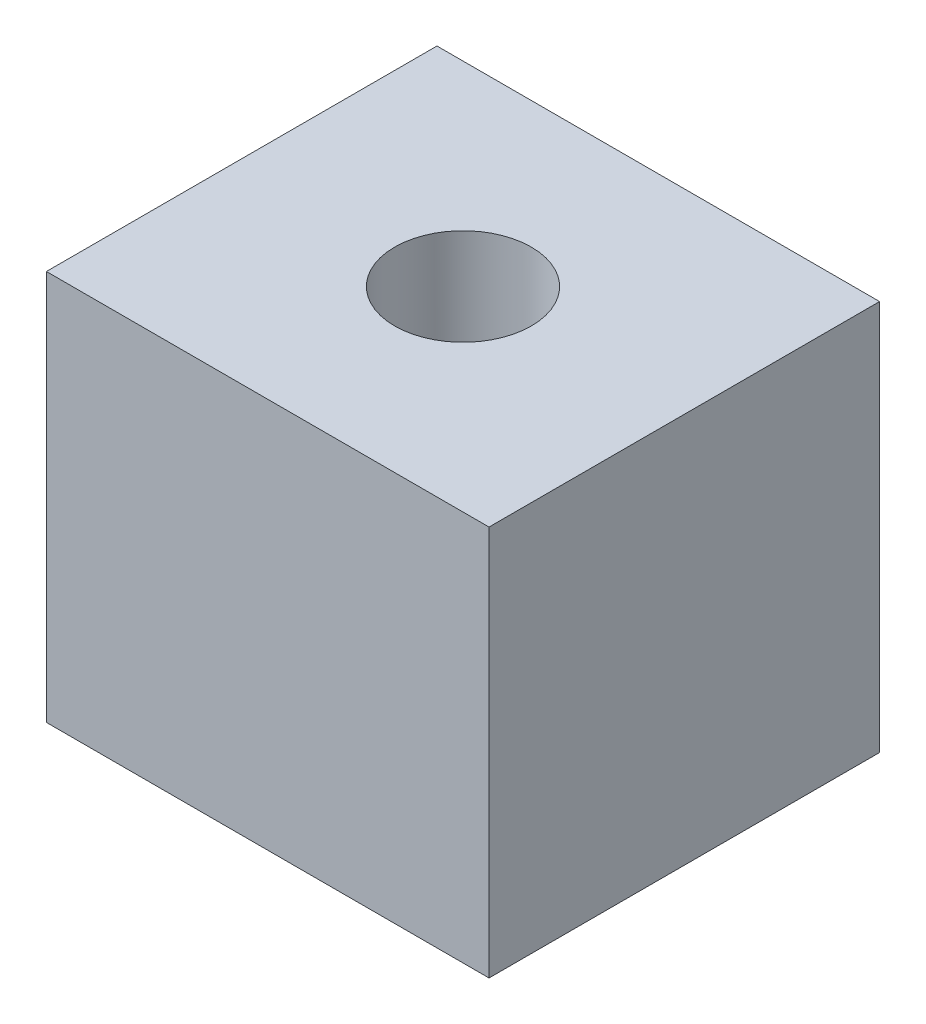
SolidWorks part; units mm, degrees
ref_plane "前视基准面" through (0, 0, 0) normal (0, 0, 1) x (1, 0, 0)
ref_plane "上视基准面" through (0, 0, 0) normal (0, 1, 0) x (1, 0, 0)
ref_plane "右视基准面" through (0, 0, 0) normal (1, 0, 0) x (0, 0, -1)
sketch "草图1" plane through (0, 0, 0) normal (0, 0, 1) x (1, 0, 0)
  line L1 (0, 0) -> (34, 0)
  line L2 (0, 0) -> (0, 30)
  line L3 (0, 30) -> (34, 30)
  line L4 (34, 0) -> (34, 30)
  dimension "D1" = 34
  dimension "D2" = 30
extrude "凸台-拉伸1" add sketch "草图1" along normal blind 30
sketch "草图2" plane through (0, 30, 0) normal (0, 1, 0) x (1, 0, 0)
  line L0 (-1.3564, -15) -> (26.4818, -15) construction
  line L1 (17, 0) -> (17, -22.7069) construction
  line L2 (34, 0) -> (0, 0) construction
  circle A0 centre (17, -15) radius 5.25
  dimension "D1" = 10.5
extrude "切除-拉伸1" cut sketch "草图2" against normal through all both and the other way through all
sketch "草图3" plane through (0, 0, 0) normal (0, 0, -1) x (-1, 0, 0)
  line L0 (-17, 30) -> (-17, 0) construction
  line L1 (-34, 30) -> (0, 30) construction
  line L2 (0, 0) -> (-34, 0) construction
  line L3 (-29, 30.6473) -> (-29, -0.9301) construction
  line L4 (-5, 30.8964) -> (-5, -1.924) construction
  line L5 (-35.2318, 15) -> (1.1384, 15) construction
  line L6 (-36.7576, 25) -> (1.5432, 25) construction
  line L7 (-36.9444, 5) -> (1.9791, 5) construction
  circle A0 centre (-29, 25) radius 1.7
  circle A1 centre (-29, 5) radius 1.7
  circle A2 centre (-5, 5) radius 1.7
  circle A3 centre (-5, 25) radius 1.7
  dimension "D5" = 3.4
  dimension "D1" = 12
  dimension "D2" = 12
  dimension "D3" = 10
  dimension "D4" = 10
extrude "切除-拉伸2" cut sketch "草图3" against normal blind 4
